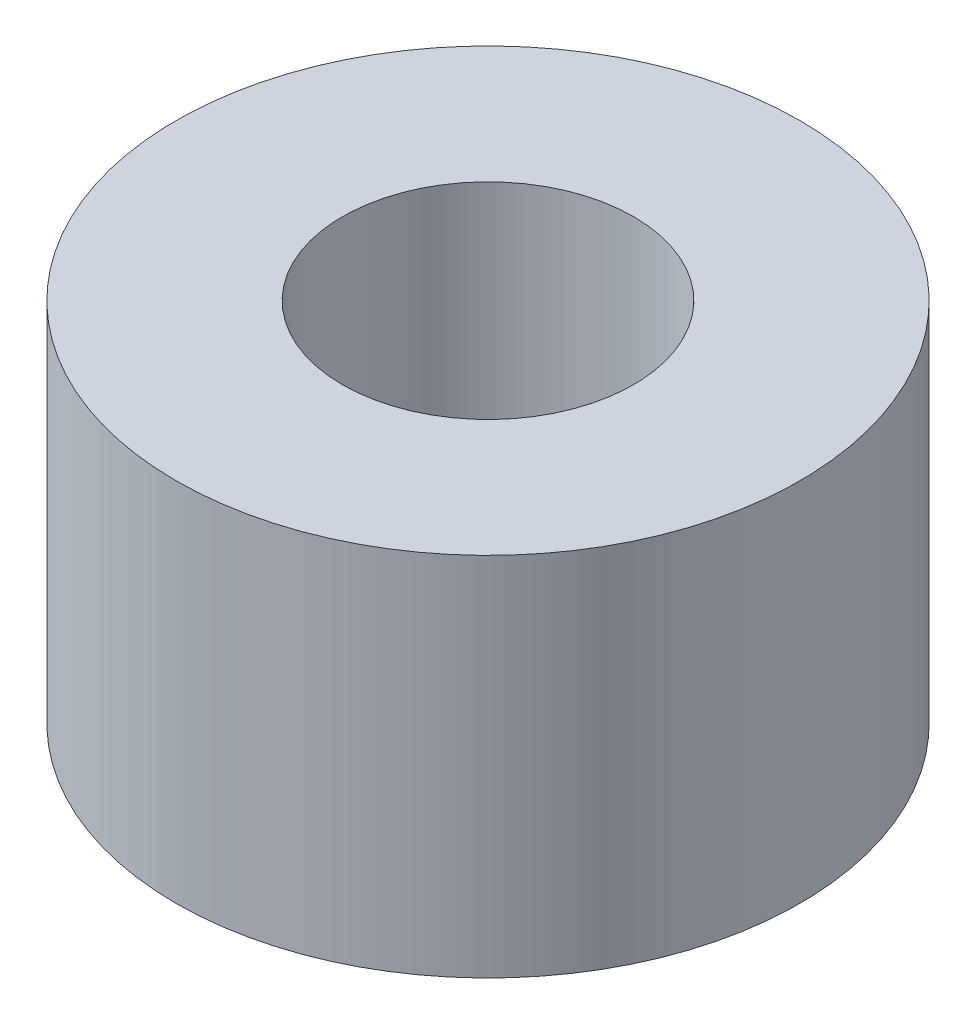
SolidWorks part; units mm, degrees
ref_plane "Front Plane" through (0, 0, 0) normal (0, 0, 1) x (1, 0, 0)
ref_plane "Top Plane" through (0, 0, 0) normal (0, 1, 0) x (1, 0, 0)
ref_plane "Right Plane" through (0, 0, 0) normal (1, 0, 0) x (0, 0, -1)
sketch "Sketch1" plane through (0, 0, 0) normal (0, 1, 0) x (1, 0, 0)
  circle A0 centre (0, 0) radius 3.75
  circle A1 centre (0, 0) radius 1.75
  dimension "D1" = 7.5
  dimension "D2" = 3.5
extrude "Boss-Extrude1" add sketch "Sketch1" along normal blind 4.4
